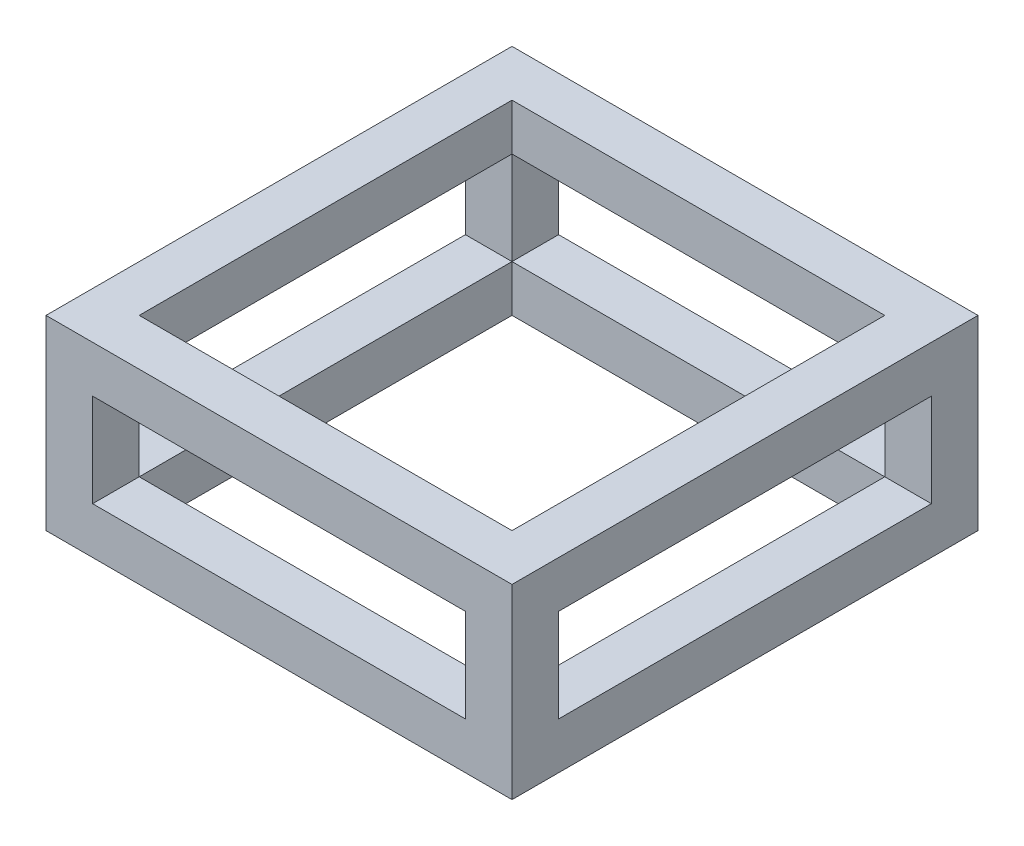
SolidWorks part; units mm, degrees
ref_plane "Front Plane" through (0, 0, 0) normal (0, 0, 1) x (1, 0, 0)
ref_plane "Top Plane" through (0, 0, 0) normal (0, 1, 0) x (1, 0, 0)
ref_plane "Right Plane" through (0, 0, 0) normal (1, 0, 0) x (0, 0, -1)
sketch "Sketch1" plane through (0, 0, 0) normal (0, 1, 0) x (1, 0, 0)
  line L1 (-75, 75) -> (75, 75)
  line L2 (-75, 75) -> (-75, -75)
  line L3 (-75, -75) -> (75, -75)
  line L4 (75, 75) -> (75, -75)
  line L5 (-75, 75) -> (75, -75) construction
  line L6 (-75, -75) -> (75, 75) construction
  line L7 (-60, 60) -> (60, 60)
  line L8 (-60, 60) -> (-60, -60)
  line L9 (-60, -60) -> (60, -60)
  line L10 (60, 60) -> (60, -60)
  line L11 (-60, 60) -> (60, -60) construction
  line L12 (-60, -60) -> (60, 60) construction
  point P0 (0, 0)
  point P6 (0, 0)
  dimension "D1" = 15
  dimension "D2" = 15
  dimension "D3" = 150
  dimension "D4" = 150
extrude "Boss-Extrude1" add sketch "Sketch1" along normal blind 15
sketch "Sketch2" plane through (0, 15, 0) normal (0, 1, 0) x (1, 0, 0)
  line L1 (-75, 75) -> (-60, 75)
  line L2 (-75, 75) -> (-75, 60)
  line L3 (-75, 60) -> (-60, 60)
  line L4 (-60, 75) -> (-60, 60)
  line L5 (60, 60) -> (75, 60)
  line L6 (60, 60) -> (60, 75)
  line L7 (60, 75) -> (75, 75)
  line L8 (75, 60) -> (75, 75)
  line L9 (75, -75) -> (60, -75)
  line L10 (75, -75) -> (75, -60)
  line L11 (75, -60) -> (60, -60)
  line L12 (60, -75) -> (60, -60)
  line L13 (-60, -60) -> (-75, -60)
  line L14 (-60, -60) -> (-60, -75)
  line L15 (-60, -75) -> (-75, -75)
  line L16 (-75, -60) -> (-75, -75)
extrude "Boss-Extrude2" add sketch "Sketch2" along normal blind 30
sketch "Sketch3" plane through (0, 45, 0) normal (0, 1, 0) x (1, 0, 0)
  line L1 (-75, 75) -> (75, 75)
  line L2 (-75, 75) -> (-75, -75)
  line L3 (-75, -75) -> (75, -75)
  line L4 (75, 75) -> (75, -75)
  line L5 (-60, 60) -> (60, 60)
  line L6 (-60, 60) -> (-60, -60)
  line L7 (-60, -60) -> (60, -60)
  line L8 (60, 60) -> (60, -60)
extrude "Boss-Extrude3" add sketch "Sketch3" along normal blind 15
